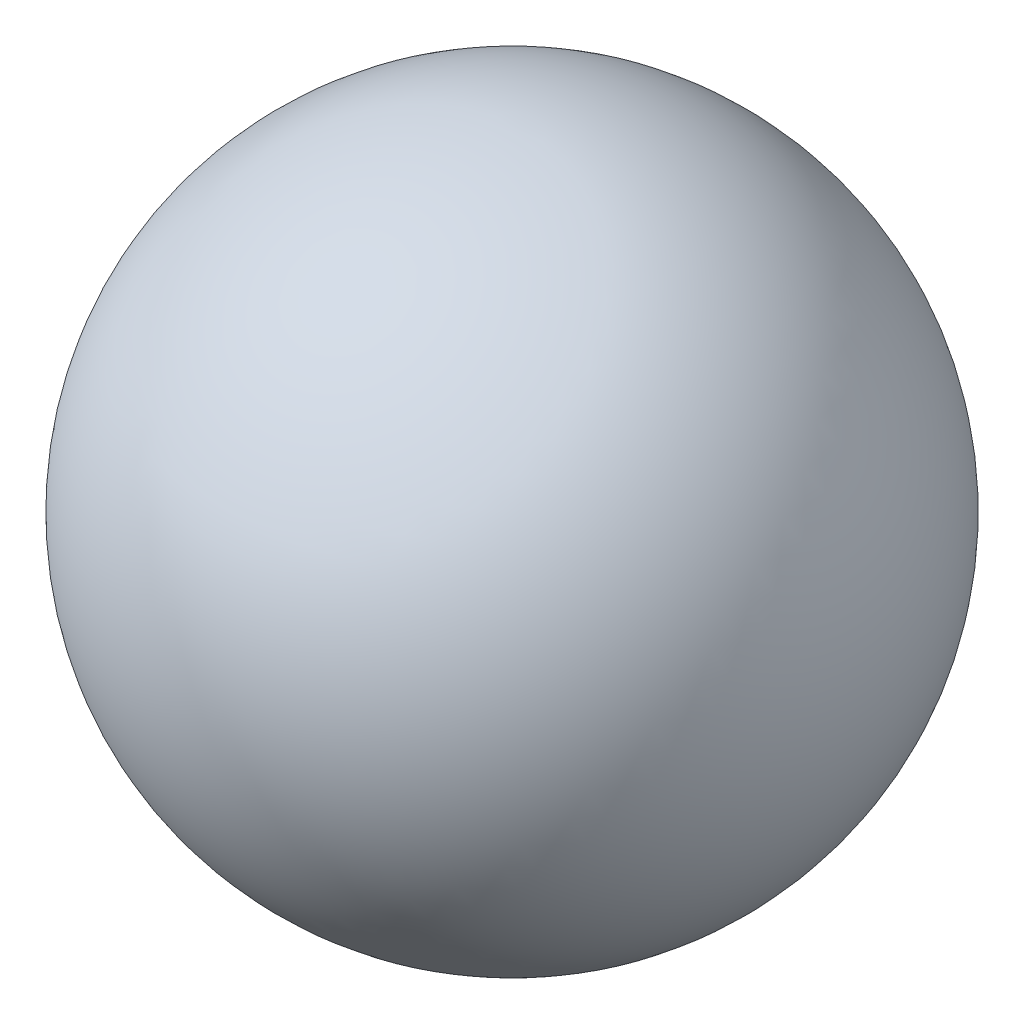
SolidWorks part; units mm, degrees
material "AISI 316 Annealed Stainless Steel Bar (SS)"
ref_plane "Front Plane" through (0, 0, 0) normal (0, 0, 1) x (1, 0, 0)
ref_plane "Top Plane" through (0, 0, 0) normal (0, 1, 0) x (1, 0, 0)
ref_plane "Right Plane" through (0, 0, 0) normal (1, 0, 0) x (0, 0, -1)
sketch "Sketch1" plane through (0, 0, 0) normal (0, 0, 1) x (1, 0, 0)
  line L0 (0, 1.75) -> (0, -1.75)
  arc A0 (0, -1.75) -> (0, 1.75) centre (0, 0) ccw
  dimension "D1" = 3.5
revolve "Revolve1" add sketch "Sketch1" angle 360 about L0
